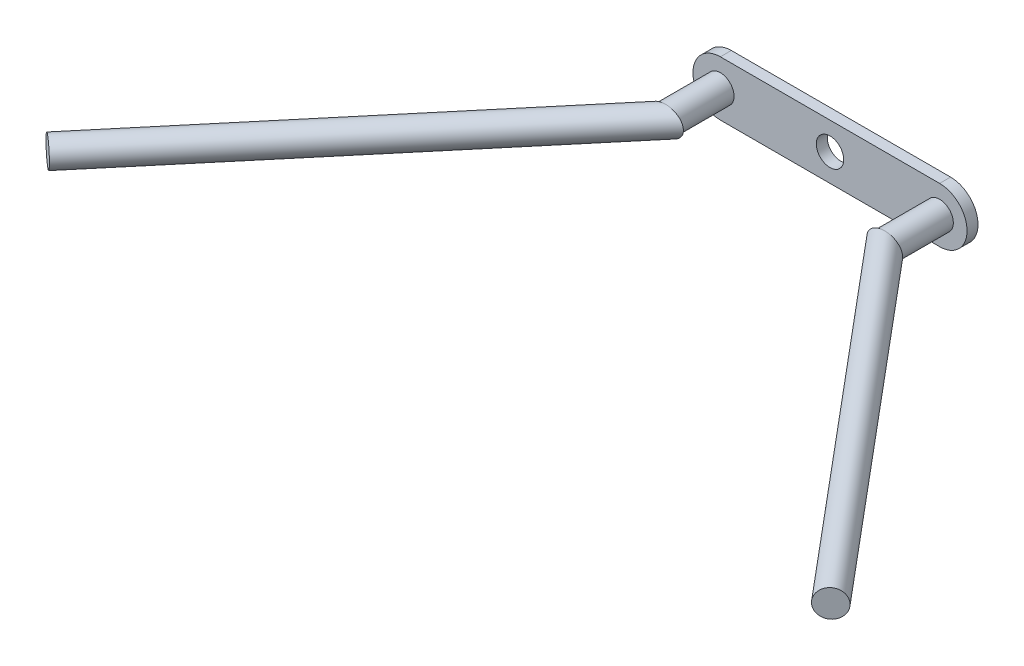
SolidWorks part; units mm, degrees
ref_plane "Front Plane" through (0, 0, 0) normal (0, 0, 1) x (1, 0, 0)
ref_plane "Top Plane" through (0, 0, 0) normal (0, 1, 0) x (1, 0, 0)
ref_plane "Right Plane" through (0, 0, 0) normal (1, 0, 0) x (0, 0, -1)
sketch "Sketch1" plane through (0, 0, 0) normal (0, 0, 1) x (1, 0, 0)
  line L0 (0, 0) -> (40, 0) construction
  line L1 (0, 5) -> (40, 5)
  line L2 (0, -5) -> (40, -5)
  arc A0 (0, 5) -> (0, -5) centre (0, 0) ccw
  arc A1 (40, -5) -> (40, 5) centre (40, 0) ccw
  circle A2 centre (20, 0) radius 2.5
  point P3 (20, 0)
  dimension "D3" = 5
  dimension "D1" = 40
  dimension "D2" = 10
extrude "Boss-Extrude1" add sketch "Sketch1" along normal blind 2
sketch "Sketch2" plane through (0, 0, 2) normal (0, 0, 1) x (1, 0, 0)
  circle A0 centre (0, 0) radius 2.5
  circle A1 centre (40, 0) radius 2.5
  circle A3 centre (20, 0) radius 2.5 construction
  dimension "D1" = 20
extrude "Boss-Extrude2" add sketch "Sketch2" along normal blind 10
sketch "Sketch3" plane through (0, 0, 0) normal (0, 1, 0) x (1, 0, 0)
  line L0 (0, -12) -> (-51.423, -73.2836)
  line L1 (-2.5, -12) -> (2.5, -12) construction
  line L2 (40, -12) -> (91.423, -73.2836)
  line L3 (37.5, -12) -> (42.5, -12) construction
  line L4 (37.5, -2) -> (37.5, -12) construction
  dimension "D1" = 80
  dimension "D2" = 80
  dimension "D3" = 220
  dimension "D4" = 80
ref_plane "Plane1" through (-51.423, 0, 73.2836) normal (-0.6428, 0, 0.766) x (0.766, 0, 0.6428)
sketch "Sketch4" plane through (-51.423, 0, 73.2836) normal (-0.6428, 0, 0.766) x (0.766, 0, 0.6428)
  circle A0 centre (0, 0) radius 2.5
  dimension "D1" = 5
extrude "Boss-Extrude3" add sketch "Sketch4" against normal up to surface (82.0977 mm away) contours A0
ref_plane "Plane2" through (91.423, 0, 73.2836) normal (0.6428, 0, 0.766) x (0.766, 0, -0.6428)
sketch "Sketch5" plane through (91.423, 0, 73.2836) normal (0.6428, 0, 0.766) x (0.766, 0, -0.6428)
  circle A0 centre (0, 0) radius 2.5
extrude "Boss-Extrude4" add sketch "Sketch5" against normal up to surface (77.9023 mm away)
